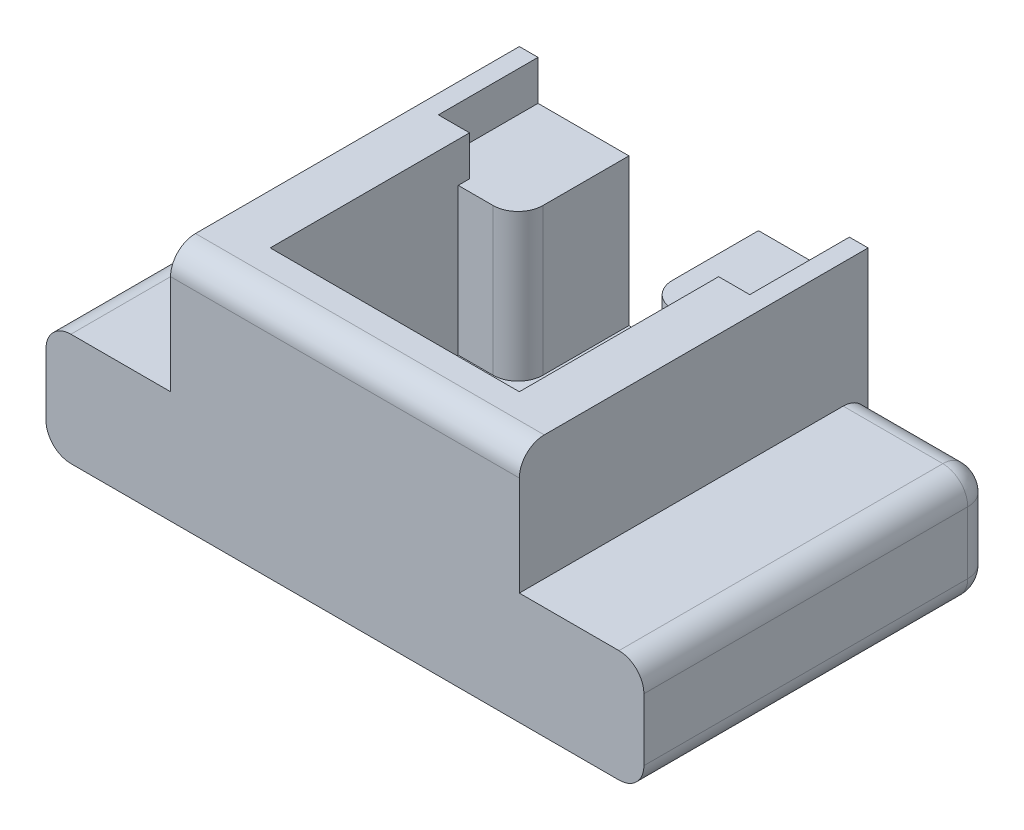
SolidWorks part; units mm, degrees
ref_plane "Front Plane" through (0, 0, 0) normal (0, 0, 1) x (1, 0, 0)
ref_plane "Top Plane" through (0, 0, 0) normal (0, 1, 0) x (1, 0, 0)
ref_plane "Right Plane" through (0, 0, 0) normal (1, 0, 0) x (0, 0, -1)
sketch "Sketch2" plane through (0, 0, 0) normal (0, 1, 0) x (1, 0, 0)
  line L0 (2.3944, 8.2488) -> (2.3944, -5.7512) construction
  line L1 (-9.6056, 8.2488) -> (14.3944, 8.2488)
  line L2 (-9.6056, 8.2488) -> (-9.6056, -5.7512)
  line L3 (-9.6056, -5.7512) -> (14.3944, -5.7512)
  line L4 (14.3944, 8.2488) -> (14.3944, -5.7512)
  dimension "D1" = 14
  dimension "D2" = 24
extrude "Boss-Extrude1" add sketch "Sketch2" along normal blind 4.5
sketch "Sketch3" plane through (0, 4.5, 0) normal (0, 1, 0) x (1, 0, 0)
  line L0 (14.3944, 8.2488) -> (-9.6056, 8.2488) construction
  line L1 (-4.6056, 8.2488) -> (9.3944, 8.2488)
  line L2 (-4.6056, 8.2488) -> (-4.6056, -5.7512)
  line L3 (-4.6056, -5.7512) -> (9.3944, -5.7512)
  line L4 (9.3944, 8.2488) -> (9.3944, -5.7512)
  line L5 (-9.6056, -5.7512) -> (14.3944, -5.7512) construction
  line L6 (14.3944, -5.7512) -> (14.3944, 8.2488) construction
  line L8 (-9.6056, 8.2488) -> (-9.6056, -5.7512) construction
  dimension "D1" = 5
  dimension "D2" = 5
extrude "Boss-Extrude2" add sketch "Sketch3" along normal blind 5
sketch "Sketch4" plane through (0, 0, -8.2488) normal (0, 0, -1) x (-1, 0, 0)
  line L0 (-2.3944, 9.5) -> (-2.3944, 0) construction
  line L1 (-9.3944, 9.5) -> (4.6056, 9.5) construction
  line L2 (-14.3944, 0) -> (9.6056, 0) construction
  line L5 (-4.9944, 4.2) -> (-4.9944, 2)
  line L6 (-4.9944, 2) -> (0.2056, 2)
  line L7 (0.2056, 4.2) -> (0.2056, 2)
  line L9 (-4.9944, 4.2) -> (-4.9944, 10.154)
  line L10 (-4.9944, 10.154) -> (0.2056, 10.154)
  line L11 (0.2056, 4.2) -> (0.2056, 10.154)
  dimension "D1" = 2.6
  dimension "D2" = 5.2
  dimension "D3" = 2.2
  dimension "D4" = 2
extrude "Cut-Extrude1" cut sketch "Sketch4" against normal blind 10
sketch "Sketch5" plane through (0, 9.5, 0) normal (0, 1, 0) x (1, 0, 0)
  line L0 (9.3944, -5.7512) -> (9.3944, 8.2488) construction
  line L1 (-2.6056, 3.7963) -> (7.3944, 3.7963)
  line L2 (-2.6056, 3.7963) -> (-2.6056, -3.7512)
  line L3 (-2.6056, -3.7512) -> (7.3944, -3.7512)
  line L4 (7.3944, 3.7963) -> (7.3944, -3.7512)
  line L5 (-4.6056, 8.2488) -> (-4.6056, -5.7512) construction
  line L6 (-4.6056, -5.7512) -> (9.3944, -5.7512) construction
  dimension "D1" = 2
  dimension "D2" = 2
  dimension "D3" = 2
extrude "Cut-Extrude2" cut sketch "Sketch5" against normal up to surface (7.5 mm away) up to face at (2.3944, 2, -3.2488)
sketch "Sketch6" plane through (0, 0, -8.2488) normal (0, 0, -1) x (-1, 0, 0)
  line L0 (-9.3944, 9.5) -> (-9.3944, 4.5) construction
  line L1 (-8.6444, 9.5) -> (3.8556, 9.5)
  line L2 (-8.6444, 9.5) -> (-8.6444, 7.9)
  line L3 (-8.6444, 7.9) -> (3.8556, 7.9)
  line L4 (3.8556, 9.5) -> (3.8556, 7.9)
  line L5 (4.6056, 9.5) -> (4.6056, 4.5) construction
  line L6 (0.2056, 9.5) -> (4.6056, 9.5) construction
  dimension "D1" = 12.5
  dimension "D2" = 0.75
  dimension "D3" = 0.75
  dimension "D4" = 0
  dimension "D5" = 1.6
extrude "Cut-Extrude3" cut sketch "Sketch6" against normal blind 4
sketch "Sketch7" plane through (0, 0, -4.2488) normal (0, 0, -1) x (-1, 0, 0)
  line L0 (-4.9944, 9.5) -> (-8.6444, 9.5) construction
  line L1 (-7.3685, 9.5) -> (2.6922, 9.5)
  line L2 (-7.3685, 9.5) -> (-7.3685, 7.9)
  line L3 (-7.3685, 7.9) -> (2.6922, 7.9)
  line L4 (2.6922, 9.5) -> (2.6922, 7.9)
  line L5 (0.2056, 7.9) -> (3.8556, 7.9) construction
extrude "Cut-Extrude4" cut sketch "Sketch7" against normal blind 1
sketch "Sketch8" plane through (7.3685, 0, 0) normal (-1, 0, 0) x (0, 0, 1)
  line L1 (-3.7963, 7.9) -> (-4.2488, 7.9)
  line L2 (-3.7963, 7.9) -> (-3.7963, 9.5)
  line L3 (-3.7963, 9.5) -> (-4.2488, 9.5)
  line L4 (-4.2488, 7.9) -> (-4.2488, 9.5)
extrude "Cut-Extrude5" cut sketch "Sketch8" against normal up to surface (0.0259 mm away) up to face at (7.3944, 5.75, -0.0226)
sketch "Sketch9" plane through (-2.6922, 0, 0) normal (1, 0, 0) x (0, 0, -1)
  line L0 (3.2488, 7.9) -> (3.2488, 9.5) construction
  line L1 (4.2488, 9.5) -> (3.2488, 9.5)
  line L2 (4.2488, 9.5) -> (4.2488, 7.9)
  line L3 (4.2488, 7.9) -> (3.2488, 7.9)
  line L4 (3.2488, 9.5) -> (3.2488, 7.9)
  line L5 (3.2488, 7.9) -> (4.2488, 7.9) construction
extrude "Boss-Extrude3" add sketch "Sketch9" along normal up to surface (0.0866 mm away) up to face at (-2.6056, 6.4667, -1.098)
fillet "Fillet1" radius 1 5 edges at (2.3944, 9.5, 5.7512) (-9.6056, 0, -1.2488) (-9.6056, 4.5, -1.2488) (14.3944, 0, -1.2488) (14.3944, 4.5, -1.2488)
fillet "Fillet2" radius 1 9 edges at (11.3944, 4.5, -8.2488) (14.1015, 4.2071, -8.2488) (-6.6056, 4.5, -8.2488) (-9.3127, 4.2071, -8.2488) (-9.6056, 2.25, -8.2488) (-9.3127, 0.2929, -8.2488) (2.3944, 0, -8.2488) (14.1015, 0.2929, -8.2488) (14.3944, 2.25, -8.2488)
fillet "Fillet3" radius 1 2 edges at (-0.2056, 4.95, -3.7963) (4.9944, 4.95, -3.7963)
